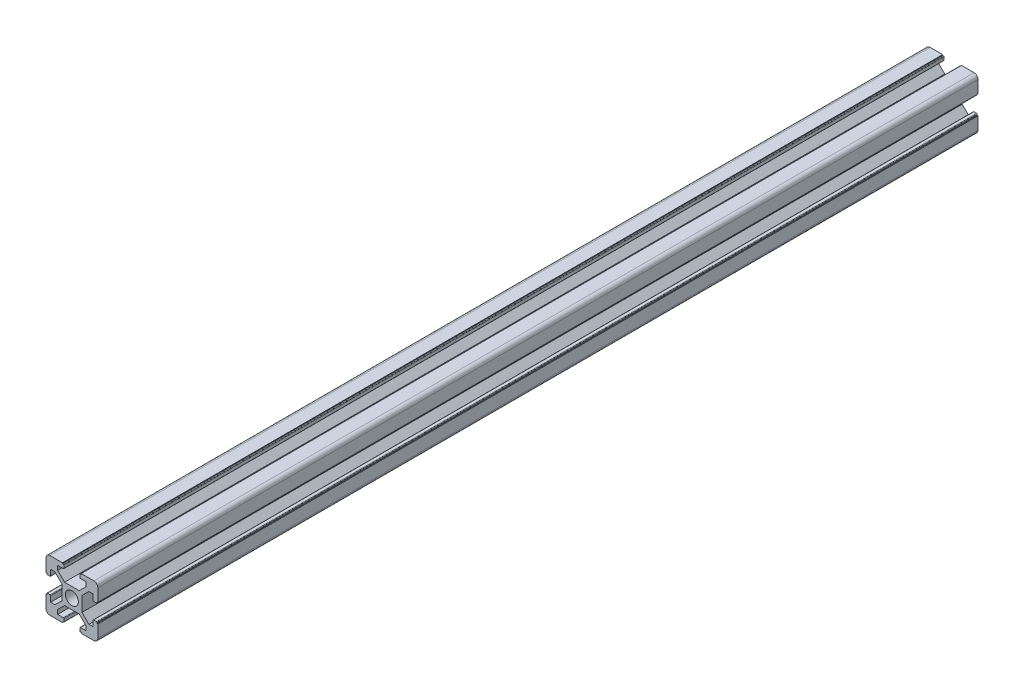
SolidWorks part; units mm, degrees
ref_plane "前视基准面" through (0, 0, 0) normal (0, 0, 1) x (1, 0, 0)
ref_plane "上视基准面" through (0, 0, 0) normal (0, 1, 0) x (1, 0, 0)
ref_plane "右视基准面" through (0, 0, 0) normal (1, 0, 0) x (0, 0, -1)
sketch "草图1" plane through (0, 0, 0) normal (0, 0, 1) x (1, 0, 0)
  line L0 (-17.5, 0) -> (33.5, 0) construction
  line L1 (0, 35.5833) -> (0, -31.0833) construction
  line L2 (3.65, 10) -> (8.5, 10)
  line L3 (10, 10) -> (10, -10) construction
  line L4 (-2.8393, 3.9) -> (2.8393, 3.9)
  line L5 (3.9, 2.8393) -> (3.9, -2.8393)
  line L6 (5.5, 8.2) -> (5.5, 6.5607)
  line L7 (3.9, 3.9) -> (10, 10) construction
  line L8 (4.4303, 3.3697) -> (6.5607, 5.5) construction
  line L9 (3.65, 10) -> (3.65, 8.2)
  line L10 (3.65, 8.2) -> (5.5, 8.2)
  line L11 (3.3697, 4.4303) -> (5.5, 6.5607) construction
  line L12 (5.5, 6.5607) -> (2.8393, 3.9)
  line L13 (6.5607, 5.5) -> (3.9, 2.8393)
  line L14 (3.3697, 4.4303) -> (9.4697, 10.5303) construction
  line L15 (4.4303, 3.3697) -> (10.5303, 9.4697) construction
  line L16 (8.2, 5.5) -> (6.5607, 5.5)
  line L17 (8.2, 3.65) -> (8.2, 5.5)
  line L18 (10, 3.65) -> (10, 8.5)
  line L19 (10, 3.65) -> (8.2, 3.65)
  line L20 (-3.3697, 4.4303) -> (-5.5, 6.5607) construction
  line L21 (-4.4303, 3.3697) -> (-6.5607, 5.5) construction
  line L22 (-3.9, 3.9) -> (-10, 10) construction
  line L23 (-10, 10) -> (-10, -10) construction
  line L24 (-10, 3.65) -> (-8.2, 3.65)
  line L25 (-10, 3.65) -> (-10, 8.5)
  line L26 (-8.2, 3.65) -> (-8.2, 5.5)
  line L27 (-8.2, 5.5) -> (-6.5607, 5.5)
  line L28 (-6.5607, 5.5) -> (-3.9, 2.8393)
  line L29 (-5.5, 6.5607) -> (-2.8393, 3.9)
  line L30 (-3.65, 8.2) -> (-5.5, 8.2)
  line L31 (-3.65, 10) -> (-3.65, 8.2)
  line L32 (-5.5, 8.2) -> (-5.5, 6.5607)
  line L33 (-3.9, 2.8393) -> (-3.9, -2.8393)
  line L34 (-3.65, 10) -> (-8.5, 10)
  line L35 (-3.9, -3.9) -> (-10, -10) construction
  line L36 (-4.4303, -3.3697) -> (-6.5607, -5.5) construction
  line L37 (-3.3697, -4.4303) -> (-5.5, -6.5607) construction
  line L38 (3.3697, -4.4303) -> (5.5, -6.5607) construction
  line L39 (4.4303, -3.3697) -> (6.5607, -5.5) construction
  line L40 (3.9, -3.9) -> (10, -10) construction
  line L41 (-3.65, -10) -> (-8.5, -10)
  line L42 (-5.5, -8.2) -> (-5.5, -6.5607)
  line L43 (-3.65, -10) -> (-3.65, -8.2)
  line L44 (-3.65, -8.2) -> (-5.5, -8.2)
  line L45 (-5.5, -6.5607) -> (-2.8393, -3.9)
  line L46 (-6.5607, -5.5) -> (-3.9, -2.8393)
  line L47 (-8.2, -5.5) -> (-6.5607, -5.5)
  line L48 (-8.2, -3.65) -> (-8.2, -5.5)
  line L49 (-10, -3.65) -> (-10, -8.5)
  line L50 (-10, -3.65) -> (-8.2, -3.65)
  line L51 (10, -3.65) -> (8.2, -3.65)
  line L52 (10, -3.65) -> (10, -8.5)
  line L53 (8.2, -3.65) -> (8.2, -5.5)
  line L54 (8.2, -5.5) -> (6.5607, -5.5)
  line L55 (6.5607, -5.5) -> (3.9, -2.8393)
  line L56 (5.5, -6.5607) -> (2.8393, -3.9)
  line L57 (3.65, -8.2) -> (5.5, -8.2)
  line L58 (3.65, -10) -> (3.65, -8.2)
  line L59 (5.5, -8.2) -> (5.5, -6.5607)
  line L60 (-2.8393, -3.9) -> (2.8393, -3.9)
  line L61 (3.65, -10) -> (8.5, -10)
  circle A0 centre (0, 0) radius 2.5
  arc A1 (-8.5, -10) -> (-10, -8.5) centre (-8.5, -8.5) cw
  arc A2 (10, -8.5) -> (8.5, -10) centre (8.5, -8.5) cw
  arc A3 (8.5, 10) -> (10, 8.5) centre (8.5, 8.5) cw
  arc A4 (-10, 8.5) -> (-8.5, 10) centre (-8.5, 8.5) cw
  point P13 (0, -3.9)
  point P42 (0, 3.9)
  point P43 (-10, 0)
  point P54 (10, 0)
  point P56 (-3.9, 0)
  point P70 (3.9, 0)
  dimension "D3" = 5
  dimension "D10" = 1.5
  dimension "D1" = 7.3
  dimension "D2" = 10
  dimension "D4" = 3.9
  dimension "D5" = 3.9
  dimension "D8" = 1.8
  dimension "D9" = 0.75
  dimension "D6" = 11
  dimension "D7" = 10
  dimension "D11" = 45
  dimension "D12" = 2.8393
extrude "凸台-拉伸2" add sketch "草图1" along normal blind 340 contours L34 A4 L25 L24 L26 L27 L28 L33 L46 L47 L48 L50 L49 A1 L41 L43 L44 L42 L45 L60 L56 L59 L57 L58 L61 A2 L52 L51 L53 L54 L55 L5 L13 L16 L17 L19 L18 A3 L2 L9 L10 L6 L12 L4 L29 L32 L30 L31
sketch "草图3" plane through (0, 0, 340) normal (0, 0, 1) x (1, 0, 0)
  line L0 (-12.6954, 0) -> (11.5012, 0) construction
  line L1 (0, 10.0863) -> (0, -11.0469) construction
  line L2 (-3.65, 8.2) -> (-3.3, 8.2)
  line L3 (3.65, 8.2) -> (3.6528, 8.2568)
  line L4 (-3.1, 8.4) -> (-3.1, 9.5)
  line L5 (3.65, 9.7) -> (3.65, 8.2)
  line L6 (-3.3, 9.7) -> (-3.65, 9.7)
  line L7 (-3.65, 8.2) -> (-3.65, 10) construction
  line L8 (-3.65, 9.7) -> (-3.65, 8.2)
  line L9 (-3.65, 8.2) -> (-3.6528, 8.2568)
  line L10 (3.3, 9.7) -> (3.65, 9.7)
  line L11 (3.1, 8.4) -> (3.1, 9.5)
  line L12 (3.65, 8.2) -> (3.3, 8.2)
  line L13 (3.65, -8.2) -> (3.3, -8.2)
  line L14 (3.1, -8.4) -> (3.1, -9.5)
  line L15 (3.3, -9.7) -> (3.65, -9.7)
  line L16 (-3.65, -8.2) -> (-3.6528, -8.2568)
  line L17 (-3.65, -9.7) -> (-3.65, -8.2)
  line L18 (-3.3, -9.7) -> (-3.65, -9.7)
  line L19 (3.65, -9.7) -> (3.65, -8.2)
  line L20 (-3.1, -8.4) -> (-3.1, -9.5)
  line L21 (3.65, -8.2) -> (3.6528, -8.2568)
  line L22 (-3.65, -8.2) -> (-3.3, -8.2)
  line L23 (0, 0) -> (9.5607, 9.5607) construction
  line L24 (-8.2, -3.65) -> (-8.2, -3.3)
  line L25 (-8.4, -3.1) -> (-9.5, -3.1)
  line L26 (-9.7, -3.3) -> (-9.7, -3.65)
  line L27 (-9.7, -3.65) -> (-8.2, -3.65)
  line L28 (-8.2, -3.65) -> (-8.2568, -3.6528)
  line L29 (8.2, 3.65) -> (8.2, 3.3)
  line L30 (8.4, 3.1) -> (9.5, 3.1)
  line L31 (9.7, 3.3) -> (9.7, 3.65)
  line L32 (9.7, 3.65) -> (8.2, 3.65)
  line L33 (8.2, 3.65) -> (8.2568, 3.6528)
  line L34 (-8.2, 3.65) -> (-8.2568, 3.6528)
  line L35 (-9.7, 3.65) -> (-8.2, 3.65)
  line L36 (-9.7, 3.3) -> (-9.7, 3.65)
  line L37 (-8.4, 3.1) -> (-9.5, 3.1)
  line L38 (-8.2, 3.65) -> (-8.2, 3.3)
  line L39 (8.2, -3.65) -> (8.2568, -3.6528)
  line L40 (9.7, -3.65) -> (8.2, -3.65)
  line L41 (9.7, -3.3) -> (9.7, -3.65)
  line L42 (8.4, -3.1) -> (9.5, -3.1)
  line L43 (8.2, -3.65) -> (8.2, -3.3)
  arc A0 (-3.1, 9.5) -> (-3.3, 9.7) centre (-3.3, 9.5) ccw
  arc A1 (-3.3, 8.2) -> (-3.1, 8.4) centre (-3.3, 8.4) ccw
  arc A2 (3.3, 8.2) -> (3.1, 8.4) centre (3.3, 8.4) cw
  arc A3 (3.1, 9.5) -> (3.3, 9.7) centre (3.3, 9.5) cw
  arc A4 (3.1, -9.5) -> (3.3, -9.7) centre (3.3, -9.5) ccw
  arc A5 (3.3, -8.2) -> (3.1, -8.4) centre (3.3, -8.4) ccw
  arc A6 (-3.3, -8.2) -> (-3.1, -8.4) centre (-3.3, -8.4) cw
  arc A7 (-3.1, -9.5) -> (-3.3, -9.7) centre (-3.3, -9.5) cw
  arc A8 (10, 8.5) -> (8.5, 10) centre (8.5, 8.5) ccw construction
  arc A9 (-9.5, -3.1) -> (-9.7, -3.3) centre (-9.5, -3.3) ccw
  arc A10 (-8.2, -3.3) -> (-8.4, -3.1) centre (-8.4, -3.3) ccw
  arc A11 (9.5, 3.1) -> (9.7, 3.3) centre (9.5, 3.3) ccw
  arc A12 (8.2, 3.3) -> (8.4, 3.1) centre (8.4, 3.3) ccw
  arc A13 (-8.2, 3.3) -> (-8.4, 3.1) centre (-8.4, 3.3) cw
  arc A14 (-9.5, 3.1) -> (-9.7, 3.3) centre (-9.5, 3.3) cw
  arc A15 (8.2, -3.3) -> (8.4, -3.1) centre (8.4, -3.3) cw
  arc A16 (9.5, -3.1) -> (9.7, -3.3) centre (9.5, -3.3) cw
  point P16 (-3.1, 9.7)
  point P19 (-3.1, 8.2)
  point P29 (3.1, 8.2)
  point P30 (3.1, 9.7)
  point P49 (3.1, -9.7)
  point P50 (3.1, -8.2)
  point P51 (-3.1, -8.2)
  point P52 (-3.1, -9.7)
  point P67 (-9.7, -3.1)
  point P68 (-8.2, -3.1)
  point P78 (9.7, 3.1)
  point P79 (8.2, 3.1)
  point P89 (-8.2, 3.1)
  point P90 (-9.7, 3.1)
  point P100 (8.2, -3.1)
  point P101 (9.7, -3.1)
  line M1 (-3.65, -10) -> (-3.65, -8.2)
  line M9 (3.65, -8.2) -> (3.65, -10)
  line M21 (8.2, 3.65) -> (10, 3.65)
  line M25 (3.65, 10) -> (3.65, 8.2)
  line M33 (-3.65, 8.2) -> (-3.65, 10)
  line M37 (-10, 3.65) -> (-8.2, 3.65)
  dimension "D3" = 0.2
  dimension "D1" = 6.2
  dimension "D2" = 1.5
extrude "凸台-拉伸3" add sketch "草图3" against normal blind 340 contours A14 L37 A13 L38 L36 M37 | L2 A1 L4 A0 L6 M33 | A3 L11 A2 L12 L10 M25 | L29 A12 L30 A11 L31 M21 | L13 A5 L14 A4 L15 M9 | A7 L20 A6 L22 L18 M1 | L43 A15 L42 A16 L41 L40 | L24 A10 L25 A9 L26 L27
